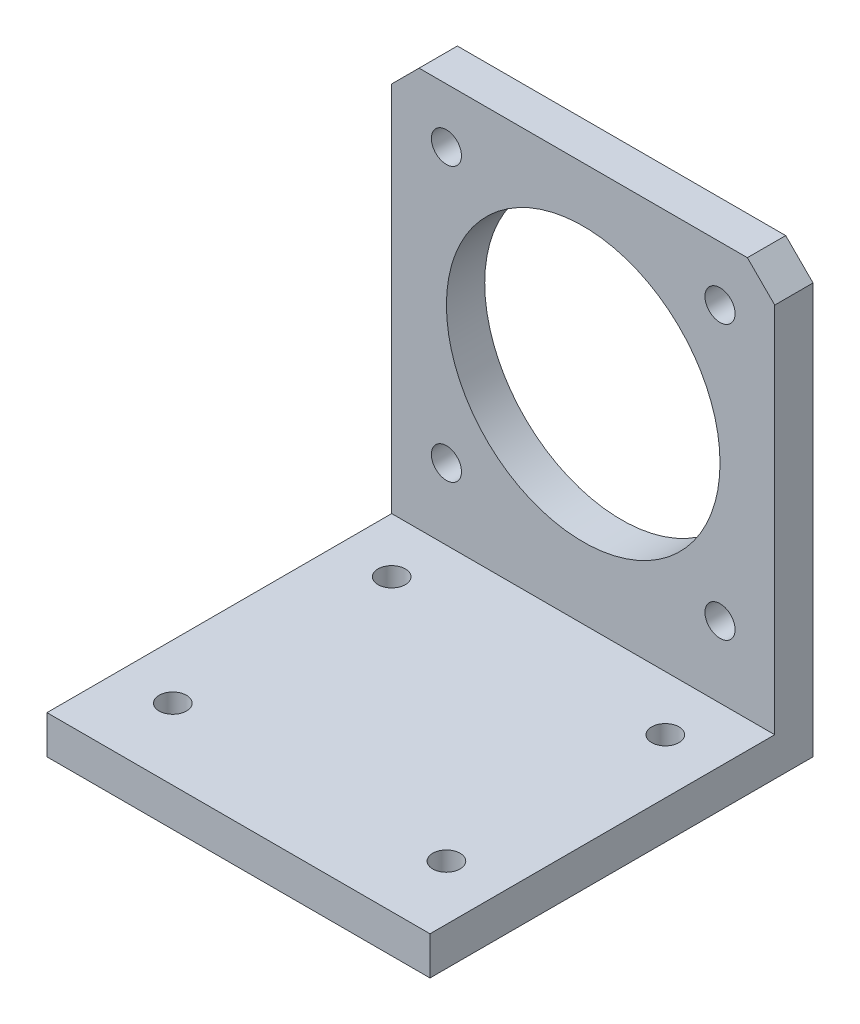
SolidWorks part; units mm, degrees
ref_plane "Front Plane" through (0, 0, 0) normal (0, 0, 1) x (1, 0, 0)
ref_plane "Top Plane" through (0, 0, 0) normal (0, 1, 0) x (1, 0, 0)
ref_plane "Right Plane" through (0, 0, 0) normal (1, 0, 0) x (0, 0, -1)
sketch "Sketch1" plane through (0, 0, 0) normal (0, 0, 1) x (1, 0, 0)
  line L1 (-35, 40) -> (35, 40)
  line L2 (-35, 40) -> (-35, -40)
  line L3 (-35, -40) -> (35, -40)
  line L4 (35, 40) -> (35, -40)
  line L5 (-35, 40) -> (35, -40) construction
  line L6 (-35, -40) -> (35, 40) construction
  circle A0 centre (-25, 30) radius 2.75
  circle A1 centre (25, 30) radius 2.75
  circle A2 centre (-25, -20) radius 2.75
  circle A3 centre (25, -20) radius 2.75
  circle A4 centre (0, 5) radius 25
  point P0 (0, 0)
  dimension "D4" = 5.5
  dimension "D6" = 2
  dimension "D9" = 50
  dimension "D1" = 70
  dimension "D2" = 80
  dimension "D3" = 10
  dimension "D5" = 10
  dimension "D8" = 5
  dimension "D7" = 2
extrude "Boss-Extrude1" add sketch "Sketch1" along normal blind 7
sketch "Sketch2" plane through (0, -40, 0) normal (0, -1, 0) x (1, 0, 0)
  line L0 (-35, 7) -> (-35, 0) construction
  line L1 (-35, 0) -> (35, 0)
  line L2 (-35, 0) -> (-35, 70)
  line L3 (-35, 70) -> (35, 70)
  line L4 (35, 0) -> (35, 70)
  line L5 (-35, 0) -> (35, 0) construction
  dimension "D1" = 70
  dimension "D2" = 0
  dimension "D3" = 70
  dimension "D4" = 0
extrude "Boss-Extrude2" add sketch "Sketch2" against normal blind 7
sketch "Sketch3" plane through (0, -33, 0) normal (0, 1, 0) x (1, 0, 0)
  line L0 (35, -7) -> (-35, -7) construction
  line L1 (-35, -70) -> (-35, -7) construction
  circle A0 centre (-25, -17) radius 2.5
  circle A1 centre (25, -17) radius 2.5
  circle A2 centre (-25, -57) radius 2.5
  circle A3 centre (25, -57) radius 2.5
  dimension "D1" = 5
  dimension "D2" = 10
  dimension "D3" = 10
  dimension "D4" = 2
  dimension "D5" = 2
extrude "Cut-Extrude1" cut sketch "Sketch3" against normal blind 7
chamfer "Chamfer1" distance 5 angle 45 2 edges at (-35, 40, 3.5) (35, 40, 3.5)
